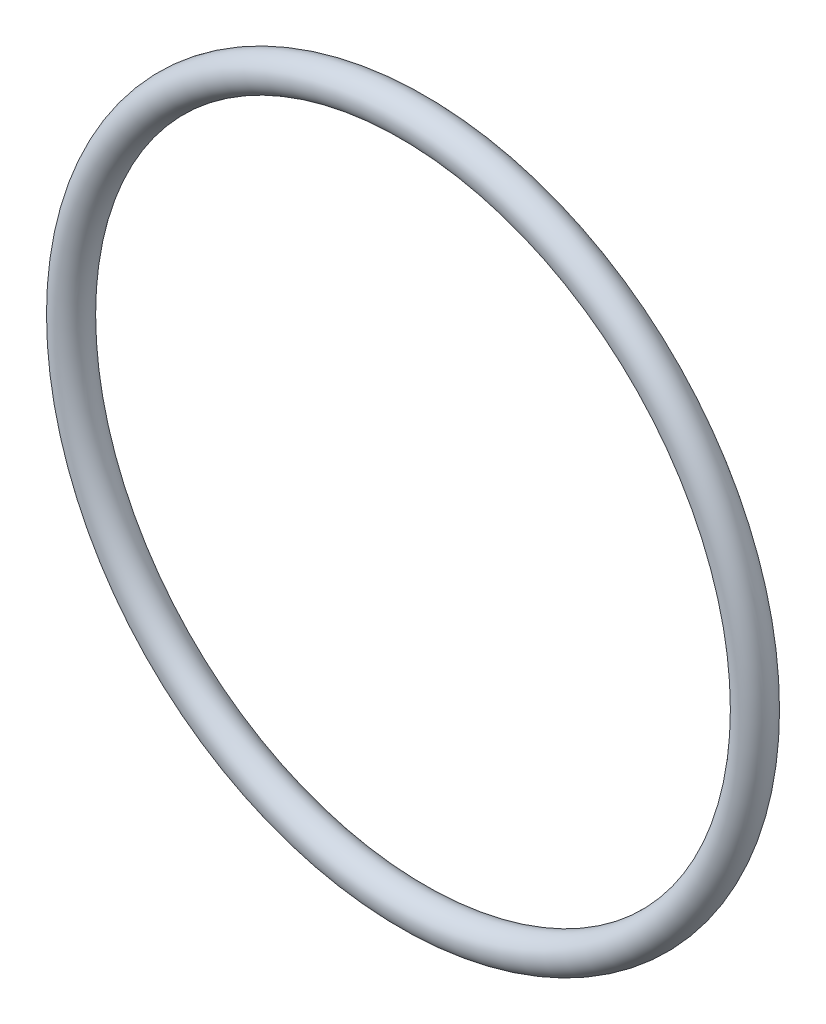
SolidWorks part; units mm, degrees
ref_plane "Front" through (0, 0, 0) normal (0, 0, 1) x (1, 0, 0)
ref_plane "Top" through (0, 0, 0) normal (0, 1, 0) x (1, 0, 0)
ref_plane "Right" through (0, 0, 0) normal (1, 0, 0) x (0, 0, -1)
sketch "Sketch1" plane through (0, 0, 0) normal (1, 0, 0) x (0, -1, 0)
  line L0 (0, -1.5) -> (0, 1.5) construction
  line L2 (-41.8, 0) -> (41.8, 0) construction
  line L3 (-28, 0) -> (28, 0) construction
  circle A0 centre (29.5, 0) radius 1.5
  point P9 (28, 0)
  point P10 (31, 0)
  point P13 (29.5, 1.5)
  point P14 (29.5, -1.5)
  dimension "Width" = 3
  dimension "ID" = 56
revolve "Revolve1" add sketch "Sketch1" angle 360 about L0
